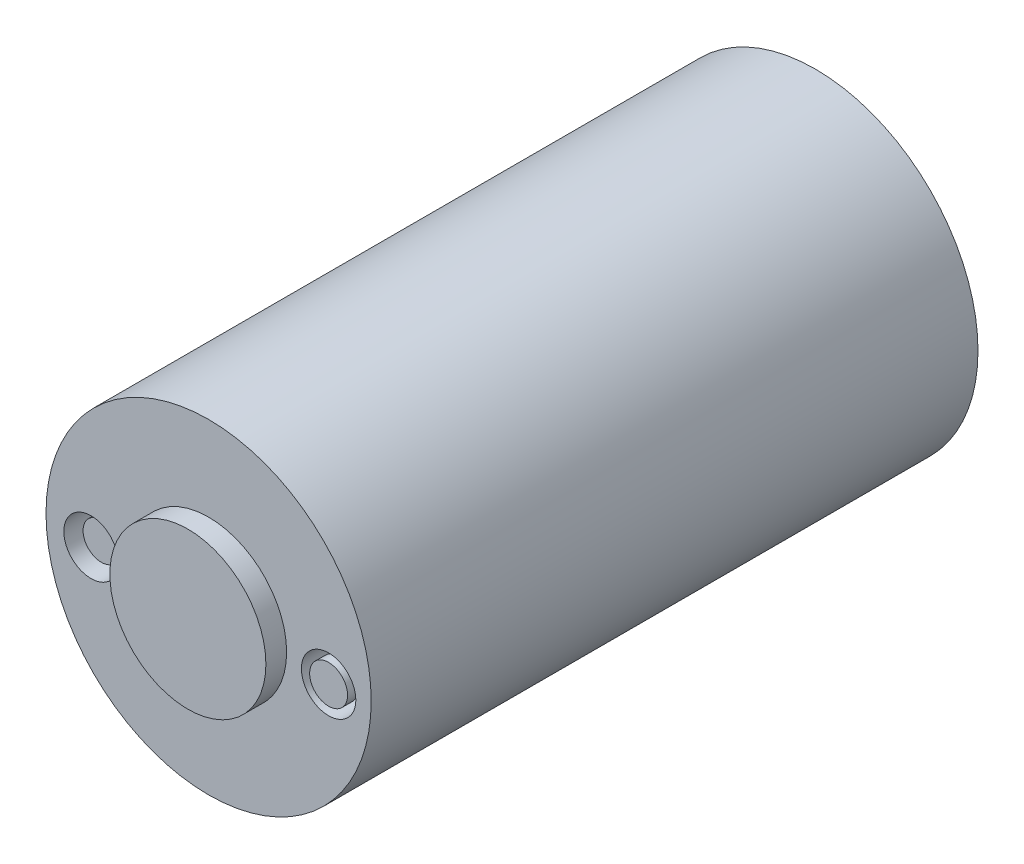
SolidWorks part; units mm, degrees
ref_plane "前视基准面" through (0, 0, 0) normal (0, 0, 1) x (1, 0, 0)
ref_plane "上视基准面" through (0, 0, 0) normal (0, 1, 0) x (1, 0, 0)
ref_plane "右视基准面" through (0, 0, 0) normal (1, 0, 0) x (0, 0, -1)
sketch "草图1" plane through (0, 0, 0) normal (0, 0, 1) x (1, 0, 0)
  circle A0 centre (-27.4092, 9.476) radius 31.385
extrude "凸台-拉伸1" add sketch "草图1" along normal blind 110.22
sketch "草图2" plane through (0, 0, 110.22) normal (0, 0, 1) x (1, 0, 0)
  circle A0 centre (-27.4092, 9.476) radius 15.06
extrude "凸台-拉伸2" add sketch "草图2" along normal blind 4
sketch "草图3" plane through (0, 0, 110.22) normal (0, 0, 1) x (1, 0, 0)
  circle A0 centre (-4.2428, 8.1643) radius 5.255
  circle A1 centre (-50.0974, 8.1643) radius 5.255
extrude "切除-拉伸1" cut sketch "草图3" against normal blind 10
sketch "草图4" plane through (0, 0, 100.22) normal (0, 0, 1) x (1, 0, 0)
  circle A0 centre (-50.0974, 8.1643) radius 3.5412
extrude "凸台-拉伸3" add sketch "草图4" along normal blind 8
sketch "草图5" plane through (0, 0, 108.22) normal (0, 0, 1) x (1, 0, 0)
  circle A0 centre (-4.2428, 8.1643) radius 3.6645
extrude "凸台-拉伸6" add sketch "草图5" along normal blind 2 separate body
sketch "草图6" plane through (0, 0, 0) normal (0, 0, -1) x (-1, 0, 0)
  circle A0 centre (27.4092, 9.476) radius 31.385
extrude "凸台-拉伸7" add sketch "草图6" along normal blind 6.91
